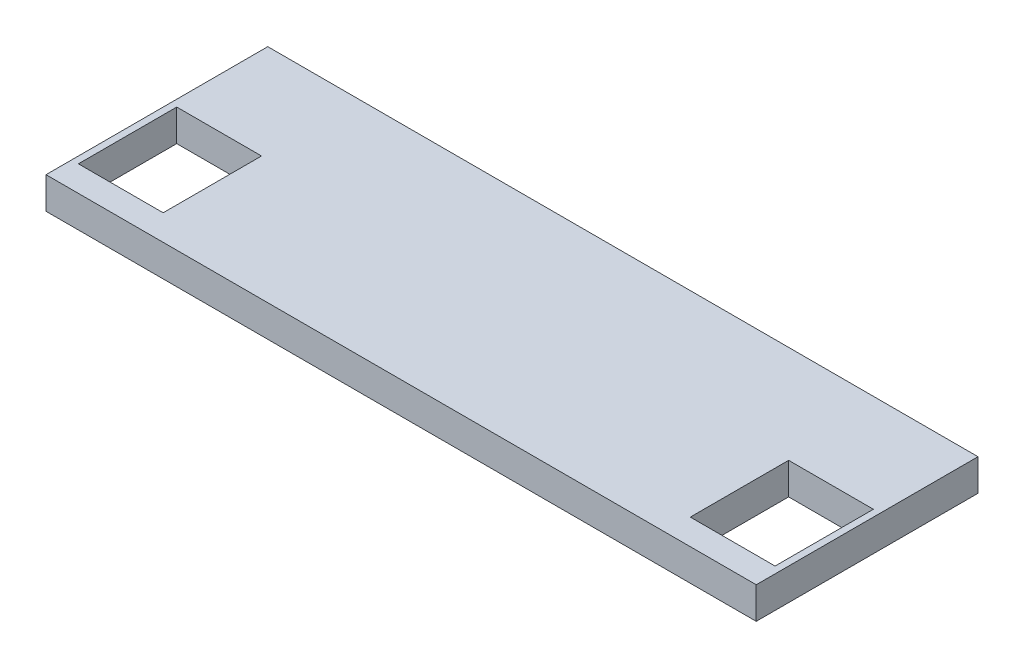
SolidWorks part; units mm, degrees
ref_plane "Front Plane" through (0, 0, 0) normal (0, 0, 1) x (1, 0, 0)
ref_plane "Top Plane" through (0, 0, 0) normal (0, 1, 0) x (1, 0, 0)
ref_plane "Right Plane" through (0, 0, 0) normal (1, 0, 0) x (0, 0, -1)
sketch "Sketch1" plane through (0, 0, 0) normal (0, 1, 0) x (1, 0, 0)
  line L0 (0, 29.0523) -> (0, 0) construction
  line L1 (0, 0) -> (36.6752, 0) construction
  line L2 (-26.6001, 16.6116) -> (-26.6001, 0)
  line L3 (-26.6001, 0) -> (26.6001, 0)
  line L4 (26.6001, 0) -> (26.6001, 16.6116)
  line L5 (26.6001, 16.6116) -> (-26.6001, 16.6116)
  line L6 (-26.6001, 8.3058) -> (26.6001, 8.3058) construction
  line L7 (19.7421, 1.919) -> (19.7421, 9.285)
  line L8 (19.7421, 9.285) -> (26.0921, 9.285)
  line L9 (26.0921, 1.919) -> (26.0921, 9.285)
  line L10 (19.7421, 1.919) -> (26.0921, 1.919)
  line L11 (19.7421, 0) -> (19.7421, 16.6116) construction
  line L12 (26.0921, 0) -> (26.0921, 16.6116) construction
  line L13 (-19.7421, 1.919) -> (-19.7421, 9.285)
  line L14 (-19.7421, 1.919) -> (-26.0921, 1.919)
  line L15 (-26.0921, 1.919) -> (-26.0921, 9.285)
  line L16 (-19.7421, 9.285) -> (-26.0921, 9.285)
  point P16 (19.7421, 5.602)
  point P23 (-19.7421, 5.602)
  dimension "D1" = 53.2003
  dimension "D2" = 16.6116
  dimension "D3" = 6.858
  dimension "D4" = 7.366
  dimension "D6" = 9.285
  dimension "D5" = 6.35
extrude "Boss-Extrude1" add sketch "Sketch1" along normal blind 2.3749 contours L7 L10 L9 L8 | L13 L16 L15 L14 | L5 L2 L3 L4
equation "\"0..0935in\"=0.1"
